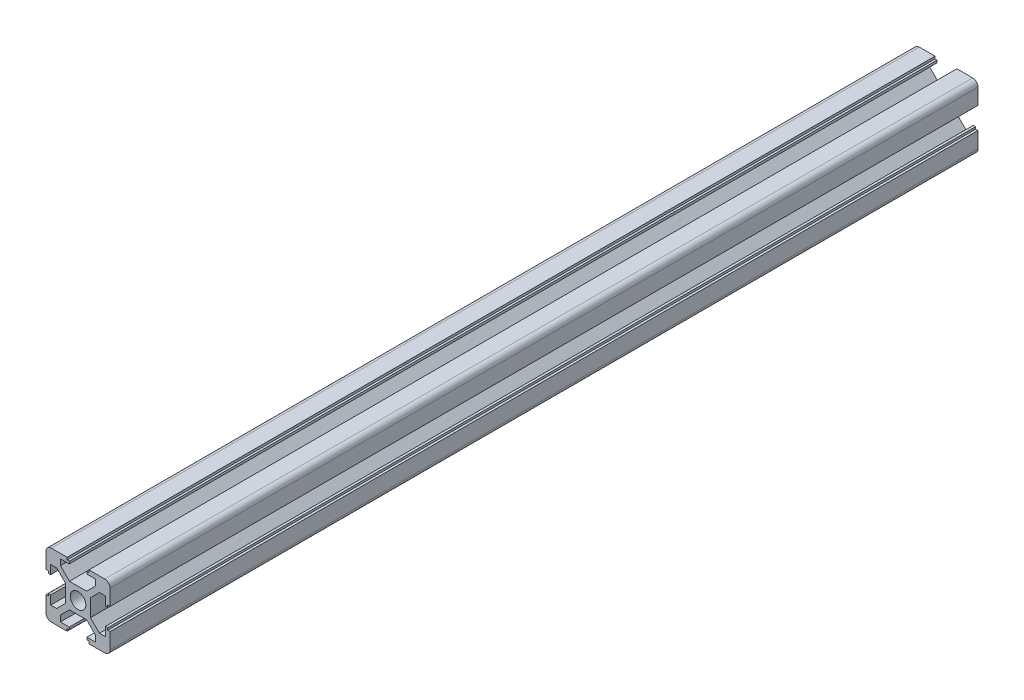
SolidWorks part; units mm, degrees
ref_plane "Front Plane" through (0, 0, 0) normal (0, 0, 1) x (1, 0, 0)
ref_plane "Top Plane" through (0, 0, 0) normal (0, 1, 0) x (1, 0, 0)
ref_plane "Right Plane" through (0, 0, 0) normal (1, 0, 0) x (0, 0, -1)
sketch "Sketch1" plane through (0, 0, 0) normal (0, 1, 0) x (1, 0, 0)
  line L0 (0, 203.2) -> (0, -203.2)
  point P4 (0, 0)
  dimension "D1" = 406.4
other "Boschrexroth BOSCH_30X30_V2(1)"
ref_plane "Plane1" through (0, 0, -203.2) normal (0, 0, 1) x (1, 0, 0)
sketch "Sketch11" plane through (0, 0, -203.2) normal (0, 0, 1) x (1, 0, 0)
  line L0 (0, 0) -> (0, 15) construction
  line L1 (0, 5.8) -> (-4.03, 5.8)
  line L2 (-15, 0) -> (0, 0) construction
  line L3 (-4.03, 5.8) -> (-8.25, 10.02)
  line L4 (-8.25, 10.02) -> (-8.25, 12.8)
  line L5 (-8.25, 12.8) -> (-4.1, 12.8)
  line L6 (-4.1, 12.8) -> (-4.1, 13.9)
  line L7 (-4.1, 13.9) -> (-5.1, 13.9)
  line L8 (-5.1, 13.9) -> (-5.1, 15)
  line L9 (-5.1, 15) -> (-12.5, 15)
  line L10 (-15, 12.5) -> (-15, 5.1)
  line L11 (-15, 5.1) -> (-13.9, 5.1)
  line L12 (-13.9, 5.1) -> (-13.9, 4.1)
  line L13 (-13.9, 4.1) -> (-12.8, 4.1)
  line L14 (-12.8, 4.1) -> (-12.8, 8.25)
  line L15 (-12.8, 8.25) -> (-10.02, 8.25)
  line L16 (-10.02, 8.25) -> (-5.8, 4.03)
  line L17 (-5.8, 4.03) -> (-5.8, 0)
  line L18 (4.1, 13.9) -> (5.1, 13.9)
  line L19 (5.1, 13.9) -> (5.1, 15)
  line L20 (10.02, 8.25) -> (5.8, 4.03)
  line L21 (12.8, 8.25) -> (10.02, 8.25)
  line L22 (12.8, 4.1) -> (12.8, 8.25)
  line L23 (13.9, 4.1) -> (12.8, 4.1)
  line L24 (13.9, 5.1) -> (13.9, 4.1)
  line L25 (15, 5.1) -> (13.9, 5.1)
  line L26 (15, 12.5) -> (15, 5.1)
  line L27 (5.1, 15) -> (12.5, 15)
  line L28 (8.25, 12.8) -> (4.1, 12.8)
  line L29 (8.25, 10.02) -> (8.25, 12.8)
  line L30 (4.03, 5.8) -> (8.25, 10.02)
  line L31 (4.1, 13.9) -> (4.1, 12.8)
  line L32 (4.03, 5.8) -> (0, 5.8)
  line L33 (5.8, 4.03) -> (5.8, 0)
  line L34 (4.1, -13.9) -> (4.1, -12.8)
  line L35 (4.1, -13.9) -> (5.1, -13.9)
  line L36 (5.1, -13.9) -> (5.1, -15)
  line L37 (4.03, -5.8) -> (8.25, -10.02)
  line L38 (8.25, -10.02) -> (8.25, -12.8)
  line L39 (8.25, -12.8) -> (4.1, -12.8)
  line L40 (5.1, -15) -> (12.5, -15)
  line L41 (15, -12.5) -> (15, -5.1)
  line L42 (15, -5.1) -> (13.9, -5.1)
  line L43 (13.9, -5.1) -> (13.9, -4.1)
  line L44 (13.9, -4.1) -> (12.8, -4.1)
  line L45 (12.8, -4.1) -> (12.8, -8.25)
  line L46 (12.8, -8.25) -> (10.02, -8.25)
  line L47 (10.02, -8.25) -> (5.8, -4.03)
  line L48 (5.8, 0) -> (5.8, -4.03)
  line L49 (-13.9, -4.1) -> (-12.8, -4.1)
  line L50 (-13.9, -5.1) -> (-13.9, -4.1)
  line L51 (-15, -5.1) -> (-13.9, -5.1)
  line L52 (-10.02, -8.25) -> (-5.8, -4.03)
  line L53 (-12.8, -8.25) -> (-10.02, -8.25)
  line L54 (-12.8, -4.1) -> (-12.8, -8.25)
  line L55 (-15, -12.5) -> (-15, -5.1)
  line L56 (-5.1, -15) -> (-12.5, -15)
  line L57 (-5.1, -13.9) -> (-5.1, -15)
  line L58 (-4.1, -13.9) -> (-5.1, -13.9)
  line L59 (-4.1, -12.8) -> (-4.1, -13.9)
  line L60 (-8.25, -12.8) -> (-4.1, -12.8)
  line L61 (-8.25, -10.02) -> (-8.25, -12.8)
  line L62 (-4.03, -5.8) -> (-8.25, -10.02)
  line L63 (-5.8, 0) -> (-5.8, -4.03)
  line L64 (-4.03, -5.8) -> (4.03, -5.8)
  line L65 (0, 0) -> (15, 0) construction
  line L66 (0, 0) -> (0, -15) construction
  arc A0 (-12.5, 15) -> (-15, 12.5) centre (-12.5, 12.5) ccw
  arc A1 (-15, -12.5) -> (-12.5, -15) centre (-12.5, -12.5) ccw
  arc A2 (12.5, -15) -> (15, -12.5) centre (12.5, -12.5) ccw
  arc A3 (15, 12.5) -> (12.5, 15) centre (12.5, 12.5) ccw
  circle A4 centre (0, 0) radius 3.65
  point P69 (-15, 15)
  point P72 (-15, -15)
  point P75 (15, -15)
  point P78 (15, 15)
  point P79 (-15, 15)
  point P81 (15, 15)
  point P83 (15, -15)
  point P84 (-15, -15)
  point P86 (0, 0)
  dimension "D15" = 2.5
  dimension "D16" = 7.3
  dimension "D1" = 15
  dimension "D2" = 2.2
  dimension "D3" = 1.1
  dimension "D4" = 1
  dimension "D5" = 8.25
  dimension "D6" = 5.1
  dimension "D7" = 7
  dimension "D8" = 2.78
  dimension "D9" = 15
  dimension "D10" = 15
  dimension "D11" = 4.03
  dimension "D12" = 4.03
  dimension "D13" = 2.5032
  dimension "D14" = 9.2
